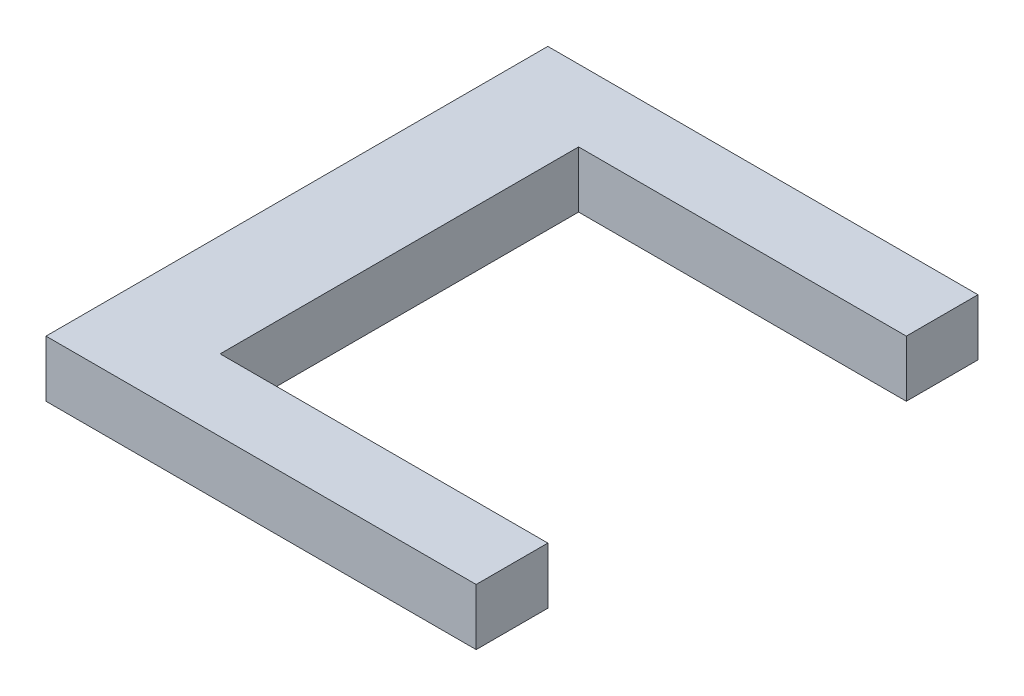
SolidWorks part; units mm, degrees
ref_plane "Front" through (0, 0, 0) normal (0, 0, 1) x (1, 0, 0)
ref_plane "Top" through (0, 0, 0) normal (0, 1, 0) x (1, 0, 0)
ref_plane "Right" through (0, 0, 0) normal (1, 0, 0) x (0, 0, -1)
sketch "Sketch1" plane through (0, 0, 0) normal (0, 1, 0) x (1, 0, 0)
  line L0 (76.2, 76.2) -> (18.1475, 76.2)
  line L1 (0, 0) -> (76.2, 0)
  line L2 (0, 0) -> (0, 88.9)
  line L3 (0, 88.9) -> (76.2, 88.9)
  line L4 (76.2, 0) -> (76.2, 88.9)
  line L5 (18.1475, 76.2) -> (18.1475, 12.7)
  line L6 (18.1475, 12.7) -> (76.2, 12.7)
  dimension "D1" = 88.9
  dimension "D2" = 76.2
  dimension "D3" = 12.7
  dimension "D4" = 12.7
extrude "Boss-Extrude1" add sketch "Sketch1" along normal blind 10 contours L6 L5 L0 L4 L3 L2 L1
